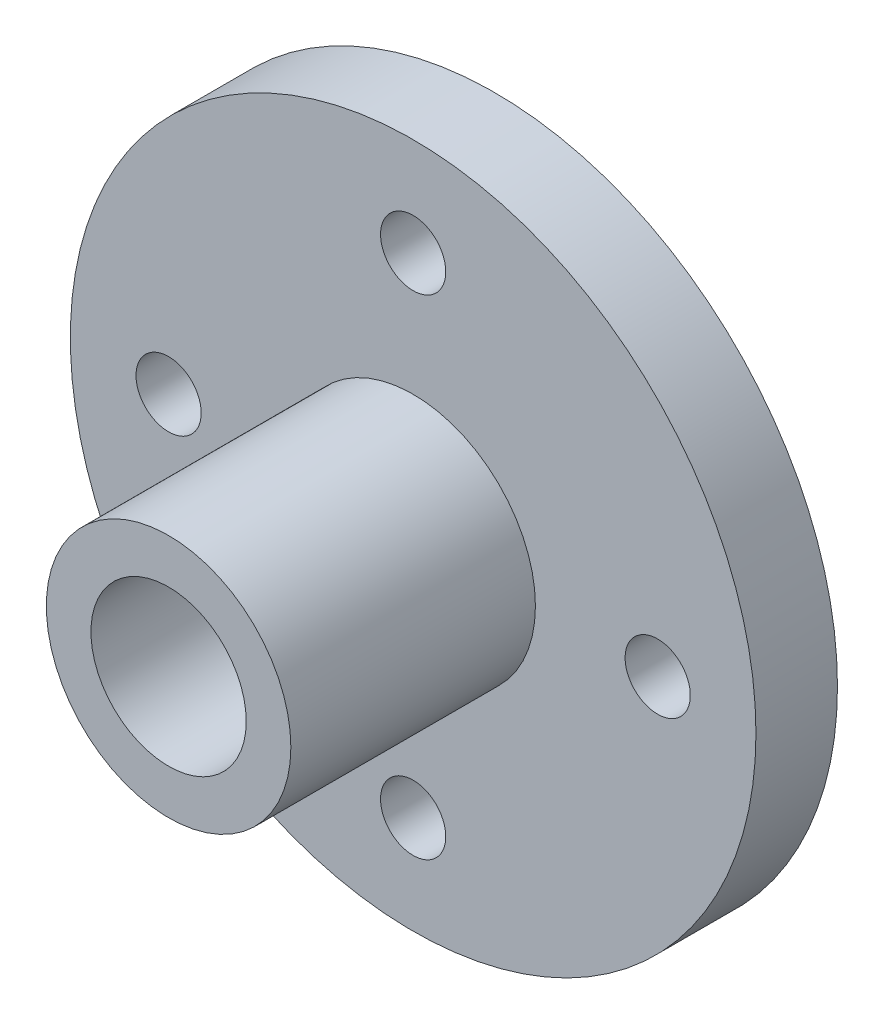
SolidWorks part; units mm, degrees
ref_plane "Front Plane" through (0, 0, 0) normal (0, 0, 1) x (1, 0, 0)
ref_plane "Top Plane" through (0, 0, 0) normal (0, 1, 0) x (1, 0, 0)
ref_plane "Right Plane" through (0, 0, 0) normal (1, 0, 0) x (0, 0, -1)
sketch "Sketch1" plane through (0, 0, 0) normal (0, 0, 1) x (1, 0, 0)
  line L0 (0, 86.3896) -> (0, -86.3896) construction
  line L1 (-124.5711, 0) -> (124.5711, 0) construction
  circle A0 centre (0, 0) radius 42.055
  circle A1 centre (0, 0) radius 9.525
  circle A2 centre (0, 30) radius 4
  circle A3 centre (-30, 0) radius 4
  circle A4 centre (0, -30) radius 4
  circle A5 centre (30, 0) radius 4
  point P4 (-30, 0)
  point P7 (0, 0)
  point P10 (0, 0)
  point P11 (0, 30)
  dimension "D1" = 84.11
  dimension "D2" = 19.05
  dimension "D5" = 8
  dimension "D6" = 8
  dimension "D3" = 30
  dimension "D4" = 30
extrude "Boss-Extrude1" add sketch "Sketch1" along normal mid plane 10
sketch "Sketch2" plane through (0, 0, 5) normal (0, 0, 1) x (1, 0, 0)
  circle A0 centre (0, 0) radius 15
  dimension "D1" = 30
extrude "Boss-Extrude2" add sketch "Sketch2" along normal blind 30
sketch "Sketch3" plane through (0, 0, 35) normal (0, 0, 1) x (1, 0, 0)
  circle A0 centre (0, 0) radius 9.525
  dimension "D1" = 19.05
extrude "Cut-Extrude1" cut sketch "Sketch3" against normal through all
